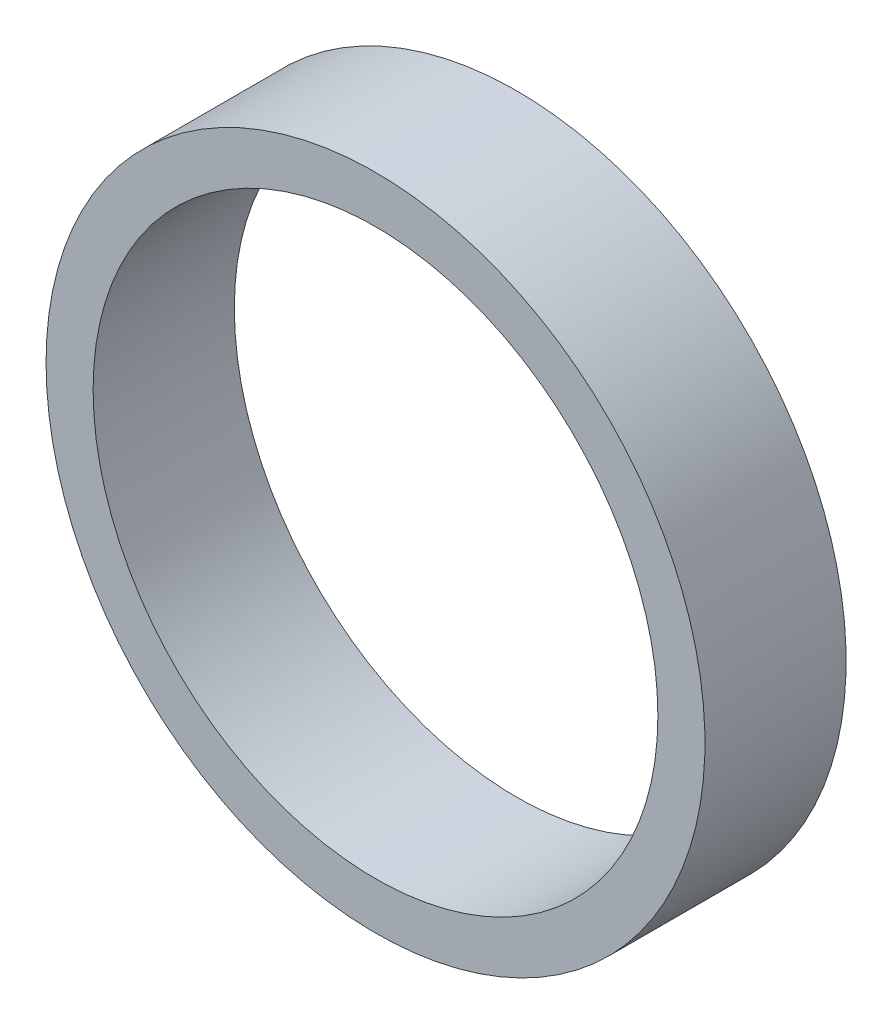
SolidWorks part; units mm, degrees
material "Plain Carbon Steel"
ref_plane "Front Plane" through (0, 0, 0) normal (0, 0, 1) x (1, 0, 0)
ref_plane "Top Plane" through (0, 0, 0) normal (0, 1, 0) x (1, 0, 0)
ref_plane "Right Plane" through (0, 0, 0) normal (1, 0, 0) x (0, 0, -1)
sketch "Sketch1" plane through (0, 0, 0) normal (0, 0, 1) x (1, 0, 0)
  circle A0 centre (0, 0) radius 22.225
  circle A1 centre (0, 0) radius 19.05
  dimension "D1" = 44.45
  dimension "D2" = 38.1
extrude "Boss-Extrude1" add sketch "Sketch1" along normal blind 9.525
